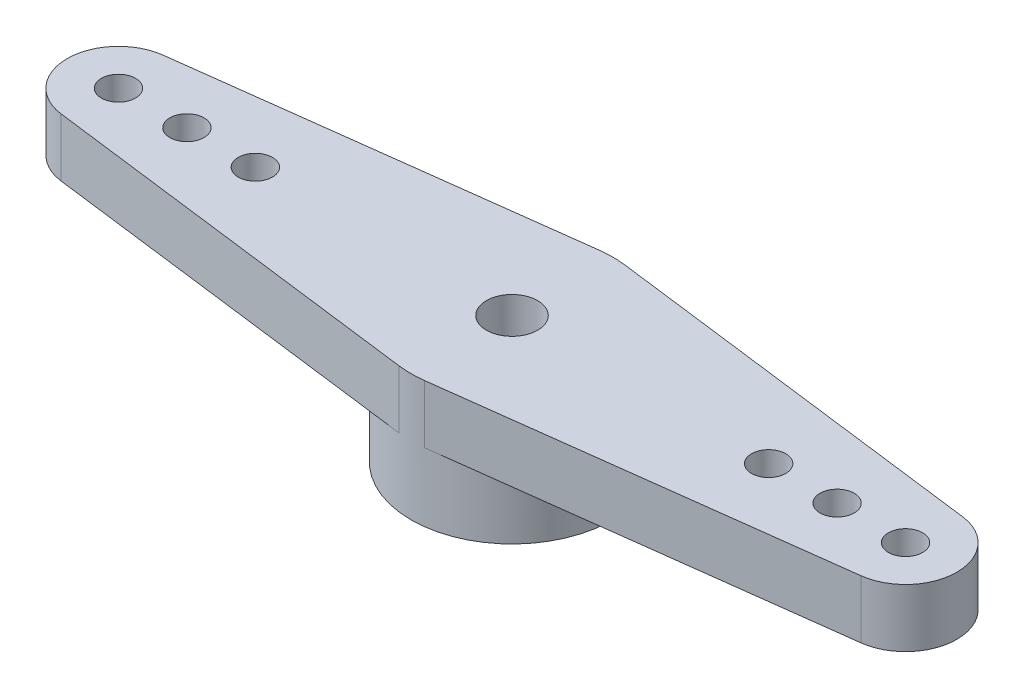
SolidWorks part; units mm, degrees
ref_plane "Front Plane" through (0, 0, 0) normal (0, 0, 1) x (1, 0, 0)
ref_plane "Top Plane" through (0, 0, 0) normal (0, 1, 0) x (1, 0, 0)
ref_plane "Right Plane" through (0, 0, 0) normal (1, 0, 0) x (0, 0, -1)
sketch "Sketch1" plane through (0, 0, 0) normal (0, 1, 0) x (1, 0, 0)
  circle A0 centre (0, 0) radius 1.9
  circle A1 centre (0, 0) radius 2.95
  dimension "D1" = 3.8
  dimension "D2" = 5.9
extrude "Boss-Extrude1" add sketch "Sketch1" along normal blind 2
sketch "Sketch2" plane through (0, 2, 0) normal (0, 1, 0) x (1, 0, 0)
  line L0 (-15.1761, 0) -> (8.3245, 0) construction
  line L1 (-13, 2.7364) -> (-13, -3.2221) construction
  line L2 (-0.372, 2.9265) -> (-11.6891, 1.488)
  line L3 (-0.372, -2.9265) -> (-11.6891, -1.488)
  line L4 (0, 3.5368) -> (0, -5.6766) construction
  line L5 (0.372, -2.9265) -> (11.6891, -1.488)
  line L6 (0.372, 2.9265) -> (11.6891, 1.488)
  arc A0 (-11.6891, 1.488) -> (-11.6891, -1.488) centre (-11.5, 0) ccw
  circle A1 centre (0, 0) radius 2.95 construction
  circle A2 centre (-11.5, 0) radius 0.5
  circle A3 centre (-9.5, 0) radius 0.5
  circle A4 centre (-7.5, 0) radius 0.5
  circle A5 centre (7.5, 0) radius 0.5
  circle A6 centre (9.5, 0) radius 0.5
  circle A7 centre (11.5, 0) radius 0.5
  arc A8 (11.6891, 1.488) -> (11.6891, -1.488) centre (11.5, 0) cw
  arc A9 (-0.372, -2.9265) -> (0.372, -2.9265) centre (0, 0) ccw
  arc A10 (0.372, 2.9265) -> (-0.372, 2.9265) centre (0, 0) ccw
  circle A11 centre (0, 0) radius 0.75
  dimension "D6" = 1
  dimension "D7" = 1
  dimension "D8" = 1
  dimension "D9" = 1.5
  dimension "D1" = 13
  dimension "D3" = 11.5
  dimension "D4" = 2
  dimension "D5" = 2
extrude "Boss-Extrude2" add sketch "Sketch2" along normal blind 1.7
